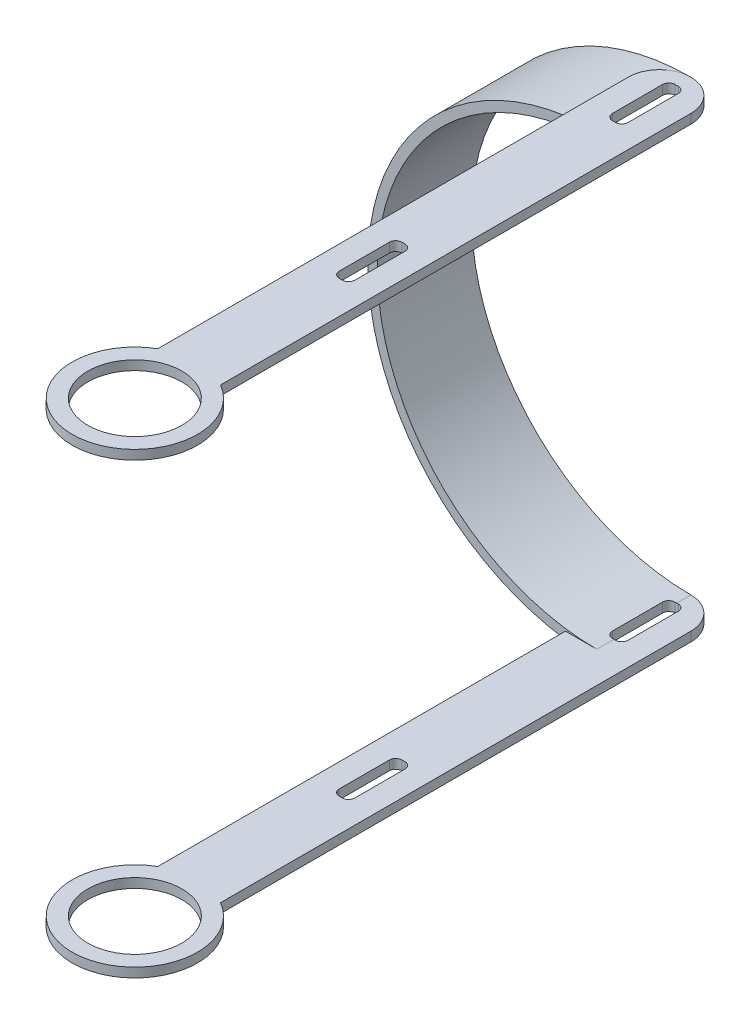
SolidWorks part; units mm, degrees
material "PVC 0.007 Plasticized"
ref_plane "Front Plane" through (0, 0, 0) normal (0, 0, 1) x (1, 0, 0)
ref_plane "Top Plane" through (0, 0, 0) normal (0, 1, 0) x (1, 0, 0)
ref_plane "Right Plane" through (0, 0, 0) normal (1, 0, 0) x (0, 0, -1)
sketch "Sketch1" plane through (0, 0, 0) normal (0, 1, 0) x (1, 0, 0)
  line L0 (0, 0) -> (0, 167.3205) construction
  line L1 (-10, 17.3205) -> (-10, 167.3205)
  line L2 (10, 17.3205) -> (10, 167.3205)
  circle A0 centre (0, 0) radius 20
  circle A1 centre (0, 0) radius 15
  arc A2 (10, 167.3205) -> (-10, 167.3205) centre (0, 167.3205) ccw
  dimension "D1" = 5
  dimension "D2" = 30
  dimension "D4" = 150
  dimension "D3" = 10
  dimension "D5" = 150
extrude "Boss-Extrude1" add sketch "Sketch1" along normal blind 3
ref_plane "Plane2" through (0, 0, -177.3205) normal (0, 0, -1) x (-1, 0, 0)
sketch "Sketch4" plane through (0, 0, -177.3205) normal (0, 0, -1) x (-1, 0, 0)
  line L1 (10, 3) -> (-10, 3) construction
  line L2 (0, 0) -> (0, 3)
  line L3 (0, 143) -> (0, 146)
  arc A0 (0, 3) -> (0, 143) centre (0, 73) ccw
  arc A1 (0, 0) -> (0, 146) centre (0, 73) ccw
  dimension "D1" = 140
  dimension "D2" = 146
extrude "Boss-Extrude5" add sketch "Sketch4" against normal blind 30
ref_plane "Plane3" through (0, 146, 0) normal (0, -1, 0) x (-1, 0, 0)
sketch "Sketch5" plane through (0, 146, 0) normal (0, -1, 0) x (-1, 0, 0)
  line L0 (0, 0) -> (0, 167.3205) construction
  line L1 (-10, -17.3205) -> (-10, 167.3205)
  line L2 (10, -17.3205) -> (10, 167.3205)
  circle A0 centre (0, 0) radius 20
  circle A1 centre (0, 0) radius 15
  arc A2 (10, 167.3205) -> (-10, 167.3205) centre (0, 167.3205) ccw
  arc A3 (-10, 17.3205) -> (10, 17.3205) centre (0, 0) ccw construction
  point P9 (0, 177.3205)
  dimension "D1" = 30
  dimension "D2" = 10
extrude "Boss-Extrude6" add sketch "Sketch5" along normal blind 3
sketch "Sketch7" plane through (0, 146, 0) normal (0, 1, 0) x (1, 0, 0)
  line L0 (0, 177.3205) -> (0, 162.8049)
  line L1 (0.5, 152.8049) -> (-0.5, 152.8049)
  line L2 (2.5, 154.8049) -> (2.5, 170.8049)
  line L3 (0.5, 172.8049) -> (-0.5, 172.8049)
  line L4 (-2.5, 154.8049) -> (-2.5, 170.8049)
  line L5 (2.5, 152.8049) -> (-2.5, 172.8049) construction
  line L6 (2.5, 172.8049) -> (-2.5, 152.8049) construction
  line L7 (0, 162.8049) -> (0, 15) construction
  line L8 (0.5, 65.6769) -> (-0.5, 65.6769)
  line L11 (2.5, 67.6769) -> (2.5, 83.6769)
  line L12 (0.5, 85.6769) -> (-0.5, 85.6769)
  line L13 (-2.5, 67.6769) -> (-2.5, 83.6769)
  line L14 (2.5, 65.6769) -> (-2.5, 85.6769) construction
  line L15 (2.5, 85.6769) -> (-2.5, 65.6769) construction
  arc A0 (0.5, 152.8049) -> (2.5, 154.8049) centre (0.5, 154.8049) ccw
  arc A1 (-0.5, 152.8049) -> (-2.5, 154.8049) centre (-0.5, 154.8049) cw
  arc A2 (2.5, 170.8049) -> (0.5, 172.8049) centre (0.5, 170.8049) ccw
  arc A3 (-0.5, 172.8049) -> (-2.5, 170.8049) centre (-0.5, 170.8049) ccw
  circle A4 centre (0, 0) radius 15 construction
  arc A7 (0.5, 65.6769) -> (2.5, 67.6769) centre (0.5, 67.6769) ccw
  arc A8 (-0.5, 65.6769) -> (-2.5, 67.6769) centre (-0.5, 67.6769) cw
  arc A9 (2.5, 83.6769) -> (0.5, 85.6769) centre (0.5, 83.6769) ccw
  arc A10 (-0.5, 85.6769) -> (-2.5, 83.6769) centre (-0.5, 83.6769) ccw
  point P0 (0, 162.8049)
  point P5 (0, 75.6769)
  point P31 (0, 0)
  point P42 (0, 0)
  point P43 (0, 0)
  point P44 (0, 130.3867)
  point P45 (0, 0)
  point P46 (-0.5, 95.0627)
  point P47 (-0.5, 75.6769)
  dimension "D3" = 2
  dimension "D1" = 5
  dimension "D2" = 20
extrude "Cut-Extrude1" cut sketch "Sketch7" against normal through all
